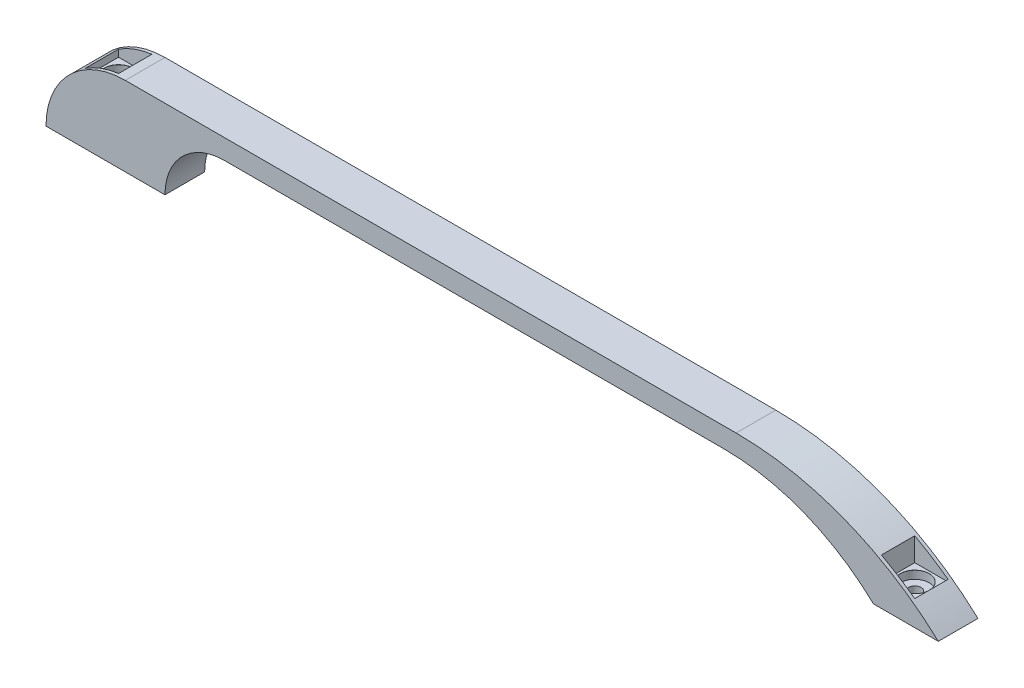
SolidWorks part; units mm, degrees
material "3.3315 (EN-AW 5005)"
ref_plane "Płaszczyzna przednia" through (0, 0, 0) normal (0, 0, 1) x (1, 0, 0)
ref_plane "Płaszczyzna górna" through (0, 0, 0) normal (0, 1, 0) x (1, 0, 0)
ref_plane "Płaszczyzna prawa" through (0, 0, 0) normal (1, 0, 0) x (0, 0, -1)
sketch "Szkic1" plane through (0, 0, 0) normal (0, 0, 1) x (1, 0, 0)
  line L1 (40, 40) -> (348.0196, 40)
  line L7 (0, 0) -> (17.8994, 0) construction
  line L10 (450, 0) -> (417.2807, 0)
  line L11 (0, 0) -> (60, 0)
  line L12 (342, 30) -> (116.3082, 30)
  line L13 (90, 30) -> (116.3082, 30)
  arc A1 (348.0196, 40) -> (450, 0) centre (348.0196, -110) cw
  arc A5 (342, 30) -> (417.2807, 0) centre (341.7821, -79.9998) cw
  arc A6 (60, 0) -> (90, 30) centre (90, 0) cw
  arc A7 (40, 40) -> (0, 0) centre (40, 0) ccw
  dimension "D3" = 60
  dimension "D5" = 150
  dimension "D6" = 110
  dimension "D8" = 30
  dimension "D9" = 40
  dimension "D1" = 450
  dimension "D2" = 40
  dimension "D4" = 252
  dimension "D7" = 32.7193
  dimension "D10" = 225.6918
extrude "Dodanie-wyciągnięcie2" add sketch "Szkic1" along normal blind 20
ref_plane "Płaszczyzna1" through (0, 30, 0) normal (0, 1, 0) x (1, 0, 0)
sketch "Szkic28" plane through (0, 30, 0) normal (0, 1, 0) x (1, 0, 0)
  line L0 (18.2, -1.6) -> (18.2, -18.4)
  line L1 (18.2, -18.4) -> (35, -18.4)
  line L2 (35, -18.4) -> (35, -1.6)
  line L3 (35, -1.6) -> (18.2, -1.6)
  line L4 (40, 0) -> (0, 0) construction
  line L5 (0, -20) -> (40, -20) construction
  line L8 (40, -20) -> (40, 0) construction
  dimension "D1" = 1.6
  dimension "D2" = 1.6
  dimension "D3" = 5
extrude "Wytnij-wyciągnięcie1" cut sketch "Szkic28" along normal blind 20
ref_plane "Płaszczyzna2" through (0, 10, 0) normal (0, 1, 0) x (1, 0, 0)
sketch "Szkic29" plane through (0, 10, 0) normal (0, 1, 0) x (1, 0, 0)
  line L0 (419.7, -18.4) -> (436.5, -18.4)
  line L1 (436.5, -18.4) -> (436.5, -1.6)
  line L2 (436.5, -1.6) -> (419.7, -1.6)
  line L3 (419.7, -1.6) -> (419.7, -18.4)
  line L4 (450, 0) -> (348.0196, 0) construction
  line L5 (348.0196, -20) -> (450, -20) construction
  line L6 (450, -20) -> (450, 0) construction
  dimension "D1" = 16.8
  dimension "D2" = 16.8
  dimension "D3" = 1.6
  dimension "D4" = 1.6
  dimension "D5" = 13.5
extrude "Wytnij-wyciągnięcie2" cut sketch "Szkic29" along normal blind 20
sketch "Szkic30" plane through (0, 30, 0) normal (0, 1, 0) x (1, 0, 0)
  line L0 (18.2, -10) -> (35, -10) construction
  line L1 (18.2, -1.6) -> (18.2, -18.4) construction
  line L2 (35, -18.4) -> (35, -1.6) construction
  line L3 (26.6, -1.6) -> (26.6, -18.4) construction
  line L4 (35, -1.6) -> (18.2, -1.6) construction
  line L5 (35, -18.4) -> (18.2, -18.4) construction
sketch "Szkic31" plane through (0, 10, 0) normal (0, 1, 0) x (1, 0, 0)
  line L0 (419.7, -10) -> (436.5, -10) construction
  line L1 (428.1, -1.6) -> (428.1, -18.4) construction
  line L2 (436.5, -1.6) -> (419.7, -1.6) construction
  line L3 (419.7, -1.6) -> (419.7, -18.4) construction
  point P11 (428.1, -10)
  point P12 (0, 0)
  point P13 (0, 0)
hole_wizard "Pogłębienie walcowe pod M6 wkręt z łbem sześciokątnym1" positions "Szkic31" profile "Szkic32" counterbore size "M6" standard "ISO"
sketch "Szkic32" plane through (428.1, 10, 10) normal (1, 0, 0) x (0, 0, 1)
  line L0 (0, 0) -> (0, 26.9228)
  line L1 (0, 26.9228) -> (3.2, 25)
  line L2 (3.2, 25) -> (3.2, 4)
  line L3 (3.2, 4) -> (7.2735, 4)
  line L5 (7.2735, 4) -> (7.2735, 0.025)
  line L6 (7.2735, 0.025) -> (7.2985, 0)
  line L7 (7.2985, 0) -> (0, 0)
  line L8 (-7.2735, 0.025) -> (-7.2985, 0) construction
  line L10 (0, 26.9228) -> (-3.2, 25) construction
  line L11 (0, -6.35) -> (0, 107.95) construction
  dimension "Średnica otworu" = 6.4
  dimension "Głębokość otworu" = 25
  dimension "Średnica pogłębienia walcowego" = 14.547
  dimension "Głębokość pogłębienia walcowego" = 4
  dimension "Średnica zewnętrznego pogłębienia stożkowego" = 14.597
  dimension "Kąt zewnętrznego pogłębienia stożkowego" = 90
  dimension "Kąt wiertła" = 118
hole_wizard "Pogłębienie walcowe pod M6 wkręt z łbem sześciokątnym2" positions "Szkic33" profile "Szkic34" counterbore size "M6" standard "ISO"
sketch "Szkic33" plane through (0, 30, 0) normal (0, 1, 0) x (1, 0, 0)
  line L0 (26.6, -1.6) -> (26.6, -18.4) construction
  point P0 (26.6, -10)
sketch "Szkic34" plane through (26.6, 30, 10) normal (1, 0, 0) x (0, 0, 1)
  line L0 (0, 0) -> (0, 41.9228)
  line L1 (0, 41.9228) -> (3.2, 40)
  line L2 (3.2, 40) -> (3.2, 4)
  line L3 (3.2, 4) -> (7.2735, 4)
  line L5 (7.2735, 4) -> (7.2735, 0.025)
  line L6 (7.2735, 0.025) -> (7.2985, 0)
  line L7 (7.2985, 0) -> (0, 0)
  line L8 (-7.2735, 0.025) -> (-7.2985, 0) construction
  line L10 (0, 41.9228) -> (-3.2, 40) construction
  line L11 (0, -6.35) -> (0, 107.95) construction
  dimension "Średnica otworu" = 6.4
  dimension "Głębokość otworu" = 40
  dimension "Średnica pogłębienia walcowego" = 14.547
  dimension "Głębokość pogłębienia walcowego" = 4
  dimension "Średnica zewnętrznego pogłębienia stożkowego" = 14.597
  dimension "Kąt zewnętrznego pogłębienia stożkowego" = 90
  dimension "Kąt wiertła" = 118
sketch "Szkic35" plane through (0, 0, 0) normal (0, 1, 0) x (1, 0, 0)
  line L0 (29.8, -10) -> (424.9, -10) construction
  circle A0 centre (26.6, -10) radius 3.2 construction
  circle A1 centre (428.1, -10) radius 3.2 construction
  dimension "D1" = 395.1
sketch "Szkic36" plane through (0, 30, 0) normal (0, 1, 0) x (1, 0, 0)
  line L0 (26.6, -10) -> (428.1, -10) construction
  line L1 (18.2, -10) -> (35, -10) construction
  dimension "D1" = 401.5
